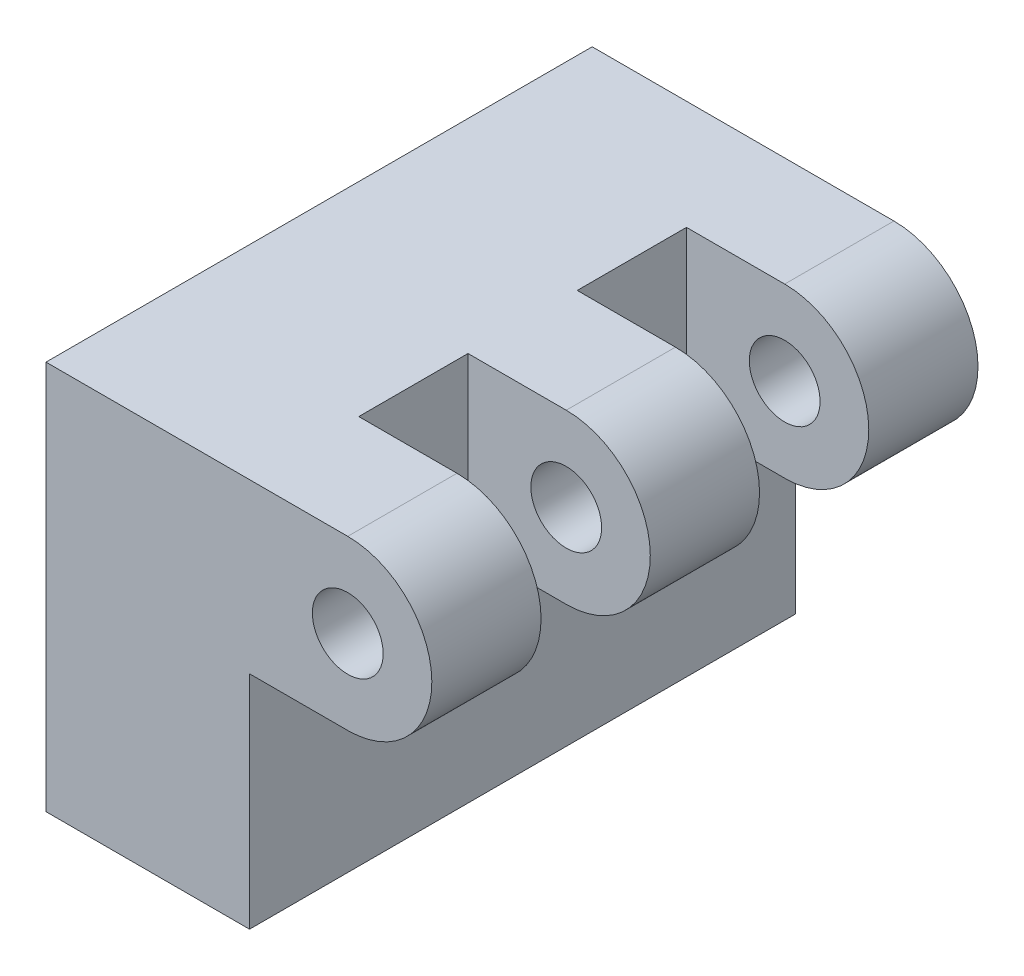
SolidWorks part; units mm, degrees
ref_plane "Front Plane" through (0, 0, 0) normal (0, 0, 1) x (1, 0, 0)
ref_plane "Top Plane" through (0, 0, 0) normal (0, 1, 0) x (1, 0, 0)
ref_plane "Right Plane" through (0, 0, 0) normal (1, 0, 0) x (0, 0, -1)
sketch "Sketch1" plane through (0, 0, 0) normal (0, 1, 0) x (1, 0, 0)
  line L5 (-40.05, 63.2864) -> (40.05, 63.2864) construction
  line L6 (-77.1348, -91.9248) -> (77.1348, 91.9248) construction
  line L8 (-69.1582, 66.8616) -> (-63.1582, 66.8616) construction
  line L9 (-69.1582, 66.8616) -> (-69.1582, 90.8254) construction
  line L10 (-69.1582, 90.8254) -> (-63.1582, 90.8254) construction
  line L11 (-63.1582, 66.8616) -> (-63.1582, 90.8254) construction
  line L12 (-77.1348, -91.9248) -> (77.1348, 91.9248) construction
  line L13 (-77.1348, -91.9248) -> (77.1348, -91.9248) construction
  line L14 (-61.8141, 89.2235) -> (77.1348, -76.3677) construction
  line L16 (-77.1348, -76.3677) -> (61.8141, 89.2235) construction
  line L17 (-77.1348, 76.3677) -> (64.0807, -91.9248) construction
  line L18 (-64.0807, -91.9248) -> (77.1348, 76.3677) construction
  line L19 (-77.1348, 91.9248) -> (-77.1348, -91.9248) construction
  line L20 (-77.1348, 91.9248) -> (77.1348, -91.9248) construction
  line L21 (77.1348, 91.9248) -> (77.1348, -91.9248) construction
  line L22 (-77.1348, 91.9248) -> (77.1348, 91.9248) construction
  line L23 (-66.1582, 94.4006) -> (-66.1582, 63.2864) construction
  line L25 (-77.1348, 91.9248) -> (77.1348, -91.9248) construction
  line L27 (-69.1582, 66.8616) -> (-63.1582, 90.8254) construction
  line L28 (-69.1582, 90.8254) -> (-63.1582, 66.8616) construction
  line L29 (-24.935, 0) -> (24.935, 0) construction
  line L30 (0, -55) -> (0, 55) construction
  line L33 (0, 0) -> (0, 4) construction
  line L34 (-19.1, 7.715) -> (19.1, 7.715) construction
  line L35 (-19.1, 7.715) -> (-19.1, -7.715) construction
  line L36 (-19.1, -7.715) -> (19.1, -7.715) construction
  line L37 (19.1, 7.715) -> (19.1, -7.715)
  line L38 (-19.1, 7.715) -> (19.1, -7.715) construction
  line L39 (-19.1, -7.715) -> (19.1, 7.715) construction
  line L40 (19.1, 7.715) -> (24.85, 7.715)
  line L41 (19.1, 7.715) -> (19.1, -7.715) construction
  line L42 (19.1, -7.715) -> (24.85, -7.715)
  line L43 (24.85, 7.715) -> (24.85, -7.715)
  point P5 (0, 0)
  point P15 (0, 0)
  point P16 (0, 0)
  dimension "D1" = 6
  dimension "D2" = 20
  dimension "D3" = 154.2697
  dimension "D4" = 183.8496
  dimension "D5" = 20
  dimension "D6" = 80.1
  dimension "D7" = 49.87
  dimension "D8" = 15.43
  dimension "D9" = 38.2
  dimension "D10" = 5.75
extrude "Boss-Extrude3" add sketch "Sketch1" along normal blind 11 separate body
sketch "Sketch3" plane through (0, 0, -7.715) normal (0, 0, -1) x (-1, 0, 0)
  line L2 (-24.85, 11) -> (-24.85, 6.2502)
  line L3 (-27.625, 11) -> (-24.85, 11)
  line L5 (-27.6537, 6.2502) -> (-24.85, 6.2502)
  circle A1 centre (-27.625, 8.625) radius 1
  arc A2 (-27.625, 11) -> (-27.6537, 6.2502) centre (-27.625, 8.625) ccw
  dimension "D1" = 4.75
  dimension "D2" = 2
  dimension "D3" = 2.775
extrude "Boss-Extrude4" add sketch "Sketch3" against normal blind 3.086
sketch "Sketch4" plane through (0, 0, 0) normal (0, 0, 1) x (1, 0, 0)
  line L6 (27.625, 11) -> (24.85, 11)
  line L7 (24.85, 11) -> (24.85, 6.2502)
  line L8 (24.85, 6.2502) -> (27.6537, 6.2502)
  line L9 (27.625, 11) -> (24.85, 11)
  line L10 (24.85, 11) -> (24.85, 6.2502)
  line L11 (24.85, 6.2502) -> (27.6537, 6.2502)
  circle A4 centre (27.625, 8.625) radius 1 construction
  arc A5 (27.6537, 6.2502) -> (27.625, 11) centre (27.625, 8.625) ccw
  arc A6 (27.6537, 6.2502) -> (27.625, 11) centre (27.625, 8.625) ccw
  circle A7 centre (27.625, 8.625) radius 1
  dimension "D1" = 0
extrude "Boss-Extrude5" add sketch "Sketch4" along normal mid plane 3.086
sketch "Sketch5" plane through (0, 0, 7.715) normal (0, 0, 1) x (1, 0, 0)
  line L0 (24.85, 6.2502) -> (27.6537, 6.2502) construction
  line L1 (27.625, 11) -> (24.85, 11) construction
  line L14 (24.85, 11) -> (24.85, 6.2502) construction
  line L18 (24.85, 6.2502) -> (27.6537, 6.2502)
  line L19 (27.625, 11) -> (24.85, 11)
  line L20 (24.85, 11) -> (24.85, 6.2502)
  circle A4 centre (27.625, 8.625) radius 1 construction
  arc A7 (27.6537, 6.2502) -> (27.625, 11) centre (27.625, 8.625) ccw construction
  circle A8 centre (27.625, 8.625) radius 1
  arc A9 (27.6537, 6.2502) -> (27.625, 11) centre (27.625, 8.625) ccw
extrude "Boss-Extrude6" add sketch "Sketch5" against normal blind 3.086
